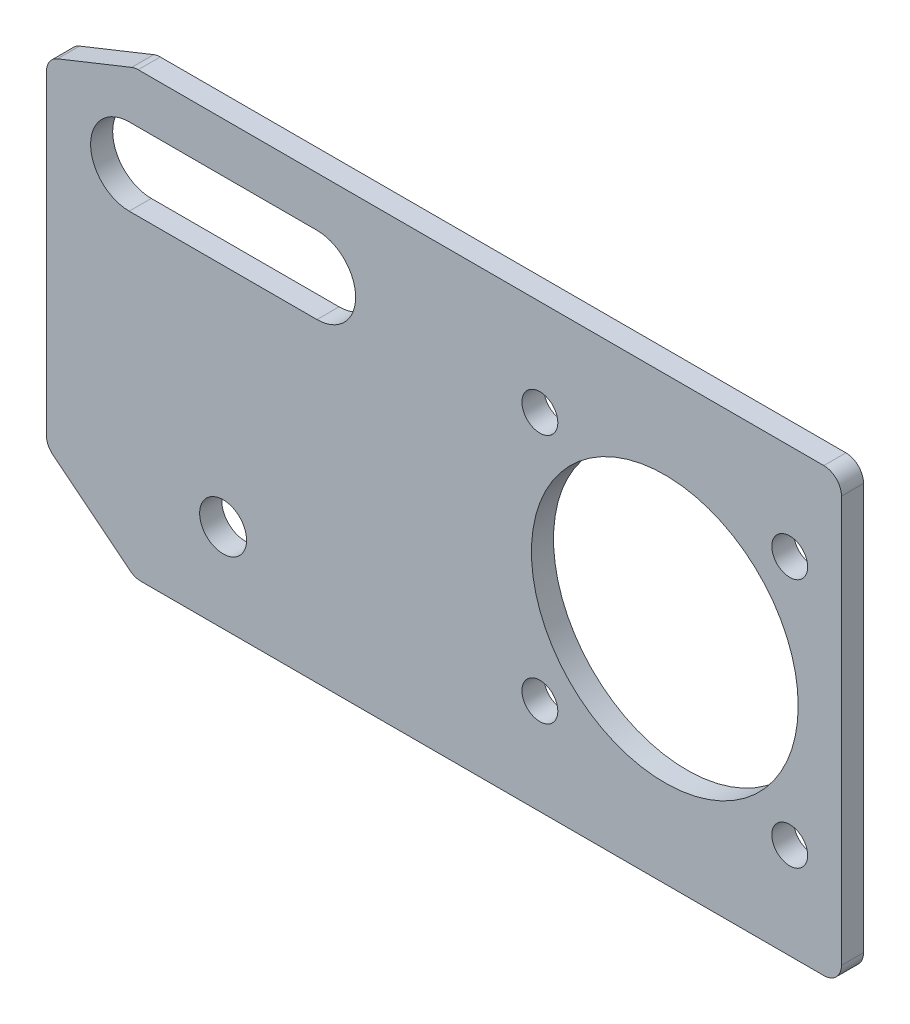
SolidWorks part; units mm, degrees
ref_plane "Front Plane" through (0, 0, 0) normal (0, 0, 1) x (1, 0, 0)
ref_plane "Top Plane" through (0, 0, 0) normal (0, 1, 0) x (1, 0, 0)
ref_plane "Right Plane" through (0, 0, 0) normal (1, 0, 0) x (0, 0, -1)
sketch "Sketch1" plane through (0, 0, 0) normal (0, 0, 1) x (1, 0, 0)
  line L0 (-12.7, 58.42) -> (0, 63.5)
  line L1 (0, 0) -> (101.6, 0)
  line L2 (0, 63.5) -> (0, 0) construction
  line L3 (0, 63.5) -> (101.6, 63.5)
  line L4 (101.6, 0) -> (101.6, 63.5)
  line L5 (-12.7, 58.42) -> (0, 58.42) construction
  line L6 (-12.7, 10.16) -> (0, 10.16) construction
  line L8 (-12.7, 58.42) -> (-12.7, 10.16)
  line L9 (-12.7, 10.16) -> (0, 0)
  dimension "D1" = 63.5
  dimension "D2" = 101.6
  dimension "D3" = 5.08
  dimension "D4" = 10.16
  dimension "D5" = 12.7
extrude "Boss-Extrude1" add sketch "Sketch1" along normal blind 3.175
sketch "Sketch2" plane through (0, 0, 3.175) normal (0, 0, 1) x (1, 0, 0)
  line L0 (101.6, 0) -> (101.6, 63.5) construction
  line L1 (0, 0) -> (101.6, 0) construction
  circle A0 centre (76.2, 31.75) radius 19.177
  dimension "D1" = 38.354
  dimension "D2" = 25.4
  dimension "D3" = 31.75
extrude "Cut-Extrude1" cut sketch "Sketch2" against normal blind 3.175
sketch "Sketch3" plane through (0, 0, 3.175) normal (0, 0, 1) x (1, 0, 0)
  line L0 (0, 0) -> (101.6, 0) construction
  line L2 (-12.7, 58.42) -> (-12.7, 10.16) construction
  circle A0 centre (12.7, 12.7) radius 3.3734
  dimension "D1" = 6.7469
  dimension "D2" = 25.4
  dimension "D3" = 12.7
extrude "Cut-Extrude2" cut sketch "Sketch3" against normal blind 3.175
sketch "Sketch4" plane through (0, 0, 3.175) normal (0, 0, 1) x (1, 0, 0)
  line L0 (-0.7937, 50.8) -> (26.1937, 50.8) construction
  line L1 (-0.7938, 56.3562) -> (26.1937, 56.3562)
  line L2 (12.7, 63.5) -> (12.7, 0) construction
  line L3 (-0.7938, 45.2438) -> (26.1937, 45.2438)
  line L4 (-12.7, 58.42) -> (-12.7, 10.16) construction
  line L5 (9.3266, 12.7) -> (16.0734, 12.7) construction
  line L6 (101.6, 63.5) -> (0, 63.5) construction
  line L7 (0, 0) -> (101.6, 0) construction
  arc A0 (-0.7938, 56.3562) -> (-0.7938, 45.2438) centre (-0.7937, 50.8) ccw
  arc A1 (26.1937, 45.2438) -> (26.1937, 56.3562) centre (26.1937, 50.8) ccw
  circle A5 centre (12.7, 12.7) radius 3.3734 construction
  point P2 (12.7, 50.8)
  point P3 (12.7, 12.7)
  point P4 (12.7, 50.8)
  point P14 (-6.35, 50.8)
  point P15 (37.6341, 50.8)
  point P17 (0, 0)
  dimension "D1" = 6.35
  dimension "D3" = 5.5562
  dimension "D2" = 50.8
extrude "Cut-Extrude3" cut sketch "Sketch4" against normal through all
fillet "Fillet1" radius 2.54 6 edges at (0, 0, 1.5875) (-12.7, 10.16, 1.5875) (-12.7, 58.42, 1.5875) (0, 63.5, 1.5875) (101.6, 0, 1.5875) (101.6, 63.5, 1.5875)
hole_wizard "13/64 (0.20313) Diameter Hole1" positions "Sketch5" profile "Sketch6" hole size "13/64" standard "ANSI Inch" end condition through all
sketch "Sketch5" plane through (0, 0, 3.175) normal (0, 0, 1) x (1, 0, 0)
  point P0 (58.2395, 49.7105)
  point P3 (94.1605, 49.7105)
  point P6 (94.1605, 13.7895)
  point P9 (58.2395, 13.7895)
sketch "Sketch6" plane through (58.2395, 49.7105, 3.175) normal (1, 0, 0) x (0, -1, 0)
  line L0 (0, 0) -> (0, 3.175)
  line L1 (0, 3.175) -> (2.5798, 3.175)
  line L2 (2.5798, 3.175) -> (2.5798, 0)
  line L5 (2.5798, 0) -> (0, 0)
  line L11 (0, -6.35) -> (0, 107.95) construction
  dimension "Thru Hole Dia." = 5.1595
  dimension "Thru Hole Depth" = 3.175
